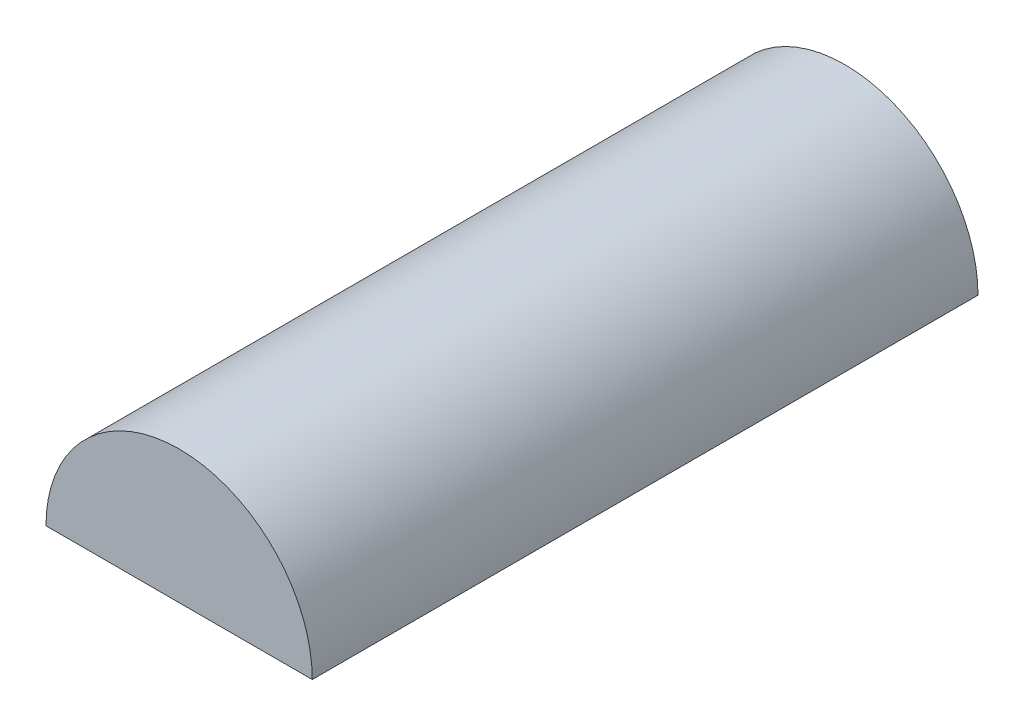
SolidWorks part; units mm, degrees
ref_plane "Front Plane" through (0, 0, 0) normal (0, 0, 1) x (1, 0, 0)
ref_plane "Top Plane" through (0, 0, 0) normal (0, 1, 0) x (1, 0, 0)
ref_plane "Right Plane" through (0, 0, 0) normal (1, 0, 0) x (0, 0, -1)
sketch "Sketch1" plane through (0, 0, 0) normal (0, 0, 1) x (1, 0, 0)
  line L0 (-100, 0) -> (100, 0)
  arc A0 (100, 0) -> (-100, 0) centre (0, 0) ccw
  point P6 (0, 0)
  dimension "D1" = 200
extrude "Boss-Extrude1" add sketch "Sketch1" along normal blind 500
